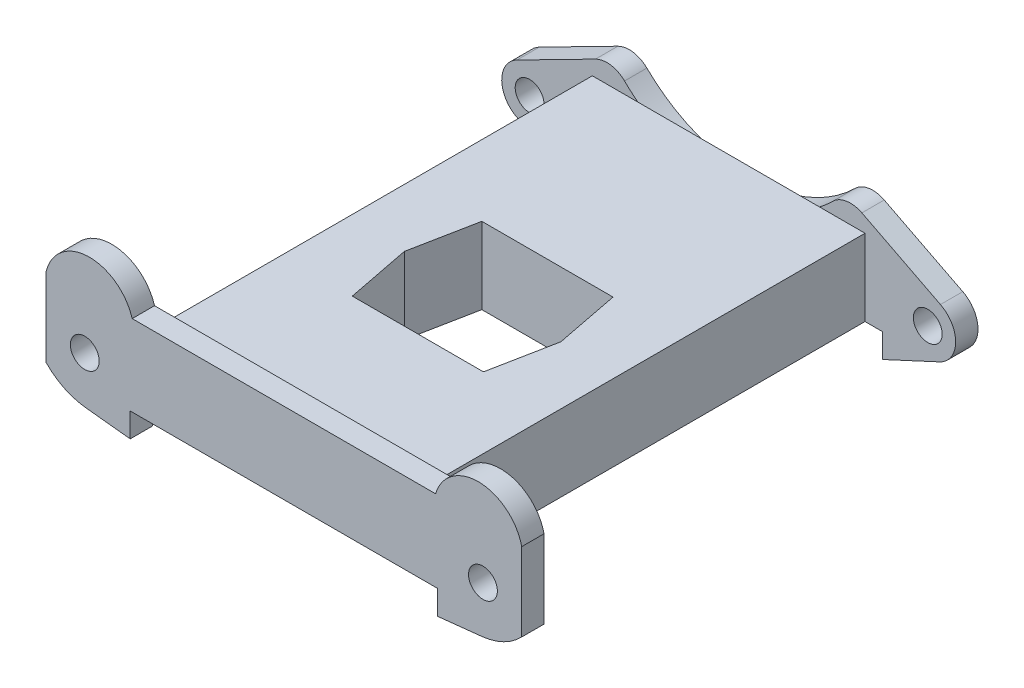
SolidWorks part; units mm, degrees
ref_plane "Front Plane" through (0, 0, 0) normal (0, 0, 1) x (1, 0, 0)
ref_plane "Top Plane" through (0, 0, 0) normal (0, 1, 0) x (1, 0, 0)
ref_plane "Right Plane" through (0, 0, 0) normal (1, 0, 0) x (0, 0, -1)
sketch "Sketch1" plane through (0, 0, 0) normal (0, 1, 0) x (1, 0, 0)
  line L0 (-8.9499, 4.0894) -> (8.9499, 4.0894)
  line L1 (18.6055, -28.829) -> (-18.6055, -28.829)
  line L2 (18.6055, -28.829) -> (18.6055, 28.829)
  line L3 (18.6055, 28.829) -> (-18.6055, 28.829)
  line L4 (-18.6055, -28.829) -> (-18.6055, 28.829)
  line L5 (18.6055, -28.829) -> (-18.6055, 28.829) construction
  line L6 (18.6055, 28.829) -> (-18.6055, -28.829) construction
  line L7 (8.9499, 4.0894) -> (10.6807, -4.7498)
  line L8 (10.6807, -4.7498) -> (8.9499, -13.589)
  line L9 (8.9499, -13.589) -> (-8.9499, -13.589)
  line L10 (-8.9499, -13.589) -> (-10.6807, -4.7498)
  line L11 (-10.6807, -4.7498) -> (-8.9499, 4.0894)
  line L12 (0, 4.0894) -> (0, -13.589) construction
  point P0 (0, 0)
  dimension "D1" = 57.658
  dimension "D2" = 37.211
  dimension "D3" = 21.3614
  dimension "D4" = 17.6784
  dimension "D5" = 15.24
  dimension "D6" = 9.0071
extrude "Boss-Extrude1" add sketch "Sketch1" along normal blind 10.4394
sketch "Sketch2" plane through (0, 0, 28.829) normal (0, 0, 1) x (1, 0, 0)
  line L0 (-20.701, 11.049) -> (20.701, 11.049)
  line L1 (-32.4612, 10.6796) -> (-32.4612, 0)
  line L2 (-20.9677, 0) -> (20.9677, 0)
  line L3 (-27.0496, -2.6515) -> (-20.9677, -3.302)
  line L4 (0, 14.523) -> (0, -4.1487) construction
  line L5 (20.9677, -3.302) -> (20.9677, 0)
  line L6 (-20.9677, -3.302) -> (-20.9677, 0)
  line L7 (27.0496, -2.6515) -> (20.9677, -3.302)
  line L8 (-18.6055, 0) -> (18.6055, 0) construction
  line L9 (32.4612, 10.6796) -> (32.4612, 0)
  arc A0 (-32.4612, 0) -> (-27.0496, -2.6515) centre (-26.1127, 6.1087) ccw
  arc A1 (20.701, 11.049) -> (32.4612, 10.6796) centre (26.5324, 9.3131) cw
  arc A2 (32.4612, 0) -> (27.0496, -2.6515) centre (26.1127, 6.1087) cw
  arc A4 (-20.701, 11.049) -> (-32.4612, 10.6796) centre (-26.5324, 9.3131) ccw
  point P3 (0, 11.049)
  point P7 (0, 0)
  point P13 (0, 11.049)
  point P15 (0, 0)
  point P19 (0, 11.049)
  point P26 (0, 11.049)
  dimension "D5" = 6.0843
  dimension "D8" = 8.8102
  dimension "D1" = 20.9677
  dimension "D2" = 32.4612
  dimension "D3" = 3.302
  dimension "D4" = 11.049
  dimension "D6" = 20.701
  dimension "D7" = 6.1166
  dimension "D9" = 10.6796
extrude "Boss-Extrude2" add sketch "Sketch2" along normal blind 3.048
sketch "Sketch3" plane through (0, 0, -28.829) normal (0, 0, -1) x (-1, 0, 0)
  line L0 (0, 6.223) -> (0, 0) construction
  line L1 (-18.6055, 0) -> (18.6055, 0) construction
  line L2 (18.175, 12.6299) -> (28.8986, 7.1591)
  line L3 (28.7697, 0.3147) -> (20.9677, -3.302)
  line L4 (20.9677, -3.302) -> (20.9677, 0)
  line L5 (20.9677, 0) -> (0, 0)
  line L6 (30.9753, 13.4698) -> (30.9753, -1.2381) construction
  line L7 (0, 13.0048) -> (21.6961, 13.0048) construction
  line L8 (0, 13.0048) -> (-21.6961, 13.0048) construction
  line L9 (-30.9753, 13.4698) -> (-30.9753, -1.2381) construction
  line L10 (-20.9677, -3.302) -> (-20.9677, 0)
  line L11 (-28.7697, 0.3147) -> (-20.9677, -3.302)
  line L12 (-18.175, 12.6299) -> (-28.8986, 7.1591)
  line L13 (-20.9677, 0) -> (0, 0)
  arc A0 (-14.2133, 12.0244) -> (14.2133, 12.0244) centre (0, 26.5348) ccw
  arc A1 (28.8986, 7.1591) -> (28.7697, 0.3147) centre (27.1687, 3.7683) cw
  arc A2 (14.2133, 12.0244) -> (18.175, 12.6299) centre (16.6152, 9.5724) cw
  arc A3 (-14.2133, 12.0244) -> (-18.175, 12.6299) centre (-16.6152, 9.5724) ccw
  arc A4 (-28.8986, 7.1591) -> (-28.7697, 0.3147) centre (-27.1687, 3.7683) ccw
  arc A5 (32.4612, 10.6796) -> (20.701, 11.049) centre (26.5324, 9.3131) ccw construction
  arc A6 (27.0496, -2.6515) -> (32.4612, 0) centre (26.1127, 6.1087) ccw construction
  dimension "D1" = 13.0048
  dimension "D2" = 3.6167
  dimension "D3" = 7.1591
  dimension "D4" = 30.9753
  dimension "D5" = 12.8003
  dimension "D6" = 8.5995
  dimension "D7" = 1.9607
extrude "Boss-Extrude3" add sketch "Sketch3" along normal blind 3.048
sketch "Sketch5" plane through (0, 0, -31.877) normal (0, 0, -1) x (-1, 0, 0)
  circle A0 centre (-27.1687, 3.7683) radius 1.9685
  circle A1 centre (27.1687, 3.7683) radius 1.9685
  arc A2 (-28.8986, 7.1591) -> (-28.7697, 0.3147) centre (-27.1687, 3.7683) ccw construction
  arc A3 (28.7697, 0.3147) -> (28.8986, 7.1591) centre (27.1687, 3.7683) ccw construction
  dimension "D2" = 3.937
extrude "Cut-Extrude1" cut sketch "Sketch5" against normal through all
sketch "Sketch6" plane through (0, 0, 0) normal (0, -1, 0) x (1, 0, 0)
  line L0 (0, 40.7775) -> (0, -39.818) construction
  line L1 (-20.9677, 31.877) -> (20.9677, 31.877) construction
  circle A0 centre (-10.0076, 24.6507) radius 1.9685
  circle A1 centre (10.0076, 24.6507) radius 1.9685
  circle A2 centre (-10.0076, -16.1417) radius 1.9685
  circle A3 centre (10.0076, -16.1417) radius 1.9685
  dimension "D1" = 3.937
  dimension "D2" = 20.0152
  dimension "D3" = 40.7924
  dimension "D4" = 7.2263
extrude "Cut-Extrude2" cut sketch "Sketch6" against normal blind 5.08
